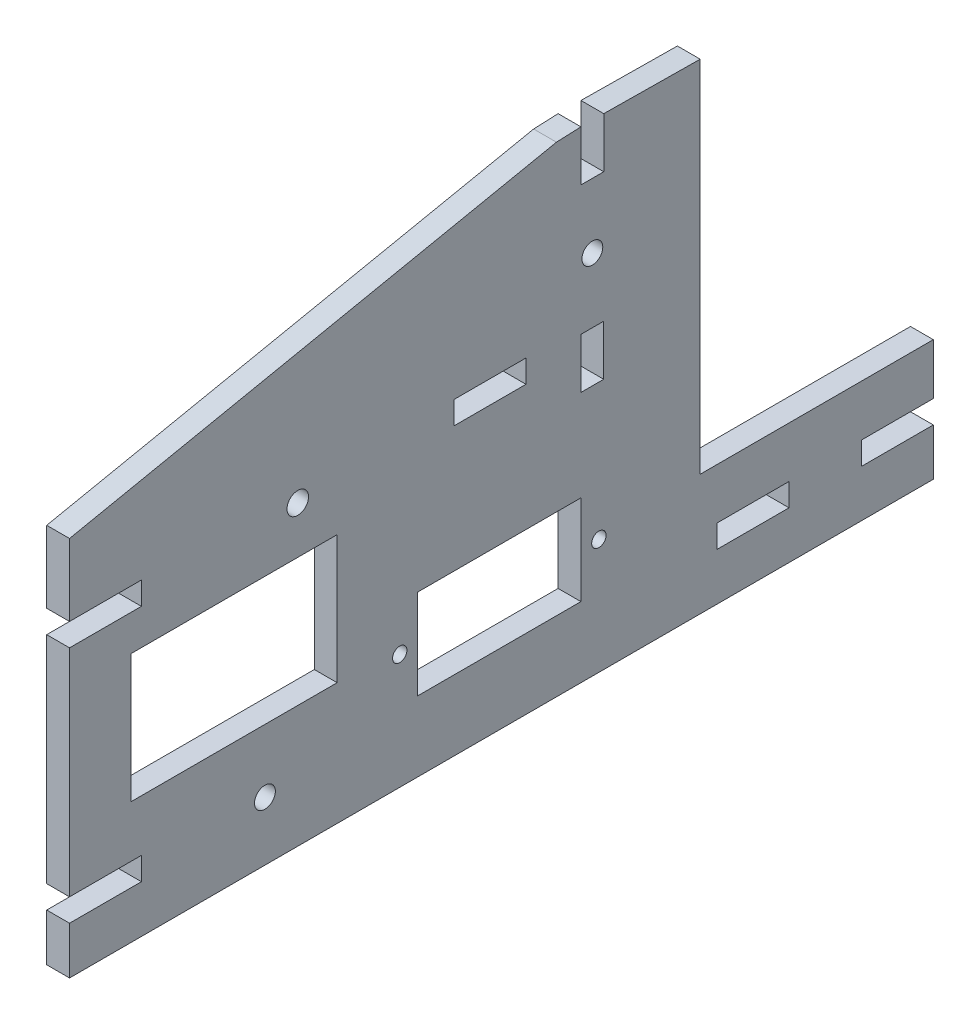
SolidWorks part; units mm, degrees
ref_plane "Front Plane" through (0, 0, 0) normal (0, 0, 1) x (1, 0, 0)
ref_plane "Top Plane" through (0, 0, 0) normal (0, 1, 0) x (1, 0, 0)
ref_plane "Right Plane" through (0, 0, 0) normal (1, 0, 0) x (0, 0, -1)
sketch "Sketch1" plane through (0, 0, 0) normal (1, 0, 0) x (0, 0, -1)
  line L0 (-106.5988, -37.0367) -> (13.5576, -37.0367)
  line L1 (-106.5988, -27.2617) -> (-106.5988, 2.7383)
  line L2 (-96.5988, 5.9133) -> (-106.5988, 5.9133)
  line L3 (-18.8656, -20.2117) -> (13.5576, -20.2117)
  line L4 (13.5576, -27.3103) -> (3.5576, -27.3103)
  line L5 (3.5576, -27.3103) -> (3.5576, -30.4853)
  line L6 (-106.5988, -30.4367) -> (-106.5988, -37.0367)
  line L7 (3.5576, -30.4853) -> (13.5576, -30.4853)
  line L9 (-58.1618, -27.2617) -> (-35.4618, -27.2617)
  line L10 (-16.5107, -27.2617) -> (-6.5107, -27.2617)
  line L11 (-6.5107, -27.2617) -> (-6.5107, -30.4367)
  line L12 (-6.5107, -30.4367) -> (-16.5107, -30.4367)
  line L13 (-106.5988, -27.2617) -> (-96.5988, -27.2617)
  line L15 (-106.5988, -30.4367) -> (-96.5988, -30.4367)
  line L16 (-96.5988, -27.2617) -> (-96.5988, -30.4367)
  line L17 (-16.5107, -30.4367) -> (-16.5107, -27.2617)
  line L18 (-18.8656, -20.2117) -> (-18.8656, 29.7883)
  line L19 (-38.8656, 29.7883) -> (-35.458, 29.9366)
  line L20 (-106.5988, 15.9133) -> (-38.8656, 29.7883)
  line L21 (-58.1618, -14.7617) -> (-35.4618, -14.7617)
  line L22 (-58.1618, -14.7617) -> (-58.1618, -27.2617)
  line L23 (-43.0988, 5.9133) -> (-53.0988, 5.9133)
  line L24 (-35.4618, -14.7617) -> (-35.4618, -27.2617)
  line L25 (-32.283, 29.9366) -> (-18.8656, 29.7883)
  line L26 (-35.458, 29.9366) -> (-35.458, 22.9366)
  line L27 (-35.458, 22.9366) -> (-32.283, 22.9366)
  line L28 (-32.283, 29.9366) -> (-32.283, 22.9366)
  line L29 (-35.4618, 4.9366) -> (-32.2868, 4.9366)
  line L30 (-35.4618, 4.9366) -> (-35.4618, -2.0634)
  line L31 (-35.4618, -2.0634) -> (-32.2868, -2.0634)
  line L32 (-32.2868, 4.9366) -> (-32.2868, -2.0634)
  line L33 (-43.0988, 5.9133) -> (-43.0988, 2.7383)
  line L34 (-43.0988, 2.7383) -> (-53.0988, 2.7383)
  line L35 (-53.0988, 5.9133) -> (-53.0988, 2.7383)
  line L37 (-96.5988, 2.7383) -> (-106.5988, 2.7383)
  line L38 (-96.5988, 5.9133) -> (-96.5988, 2.7383)
  line L39 (-106.5988, 5.9133) -> (-106.5988, 15.9133)
  line L40 (-98.074, -2.239) -> (-69.3724, -2.239)
  line L41 (-98.074, -2.239) -> (-98.074, -20.075)
  line L42 (-98.074, -20.075) -> (-69.3724, -20.075)
  line L43 (-69.3724, -2.239) -> (-69.3724, -20.075)
  line L50 (13.5576, -27.3103) -> (13.5576, -20.2117)
  line L51 (13.5576, -30.4853) -> (13.5576, -37.0367)
  circle A0 centre (-79.4188, -28.8492) radius 1.45
  circle A2 centre (-60.6618, -21.0117) radius 1
  circle A3 centre (-32.9618, -21.0117) radius 1
  circle A4 centre (-33.8705, 13.9366) radius 1.45
  circle A5 centre (-74.8488, 4.3258) radius 1.5
  point P4 (-96.5988, -28.8492)
  point P50 (-33.8705, 22.9366)
  point P51 (-53.0988, 4.3258)
  dimension "D7" = 27.18
  dimension "D20" = 2.5
  dimension "D10" = 3.175
  dimension "D27" = 16
  dimension "D3" = 10
  dimension "D4" = 32
  dimension "D5" = 10
  dimension "D6" = 6.25
  dimension "D8" = 20
  dimension "D9" = 3.175
  dimension "D11" = 10
  dimension "D12" = 10
  dimension "D13" = 2.5
  dimension "D14" = 30
  dimension "D15" = 10
  dimension "D16" = 3.175
  dimension "D17" = 6.6
  dimension "D18" = 22.7
  dimension "D19" = 12.5
  dimension "D21" = 7
  dimension "D22" = 3.175
  dimension "D23" = 3.175
  dimension "D24" = 7
  dimension "D25" = 6.25
  dimension "D26" = 3.175
  dimension "D28" = 50
  dimension "D29" = 10
  dimension "D30" = 3.175
  dimension "D31" = 90.0882
  dimension "D32" = 120.1564
  dimension "D34" = 31.75
extrude "Extrude1" add sketch "Sketch1" along normal blind 3.175
